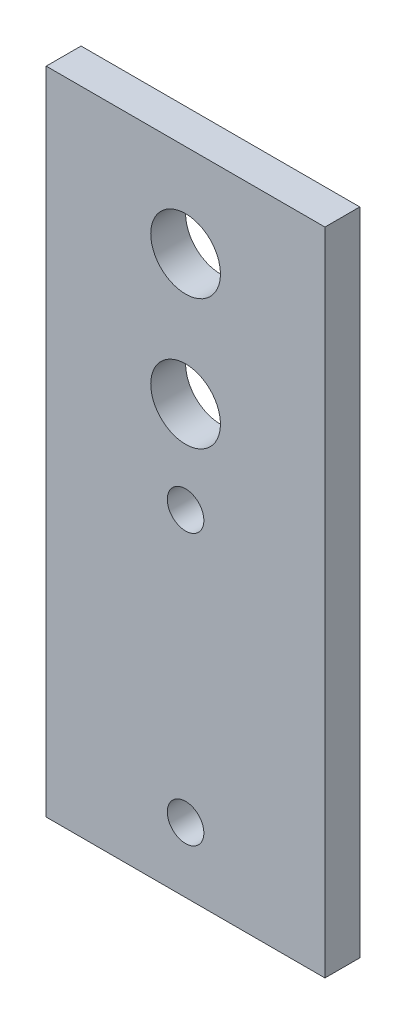
SolidWorks part; units mm, degrees
ref_plane "Front Plane" through (0, 0, 0) normal (0, 0, 1) x (1, 0, 0)
ref_plane "Top Plane" through (0, 0, 0) normal (0, 1, 0) x (1, 0, 0)
ref_plane "Right Plane" through (0, 0, 0) normal (1, 0, 0) x (0, 0, -1)
sketch "Sketch1" plane through (0, 0, 0) normal (0, 0, 1) x (1, 0, 0)
  line L0 (19.05, 45.89) -> (19.05, 8.89) construction
  line L1 (0, 0) -> (38.1, 0)
  line L2 (0, 0) -> (0, 88.9)
  line L3 (0, 88.9) -> (38.1, 88.9)
  line L4 (38.1, 0) -> (38.1, 88.9)
  circle A2 centre (19.05, 8.89) radius 2.5
  circle A3 centre (19.05, 45.89) radius 2.5
  circle A4 centre (19.05, 76.2) radius 4.7625
  circle A5 centre (19.05, 58.42) radius 4.7625
  point P5 (19.05, 0)
  point P14 (19.05, 88.9)
  dimension "D3" = 5
  dimension "D4" = 8.89
  dimension "D5" = 5
  dimension "D6" = 9.525
  dimension "D1" = 38.1
  dimension "D2" = 88.9
  dimension "D7" = 37
  dimension "D8" = 17.78
  dimension "D9" = 12.7
extrude "Boss-Extrude1" add sketch "Sketch1" along normal blind 4.7625
